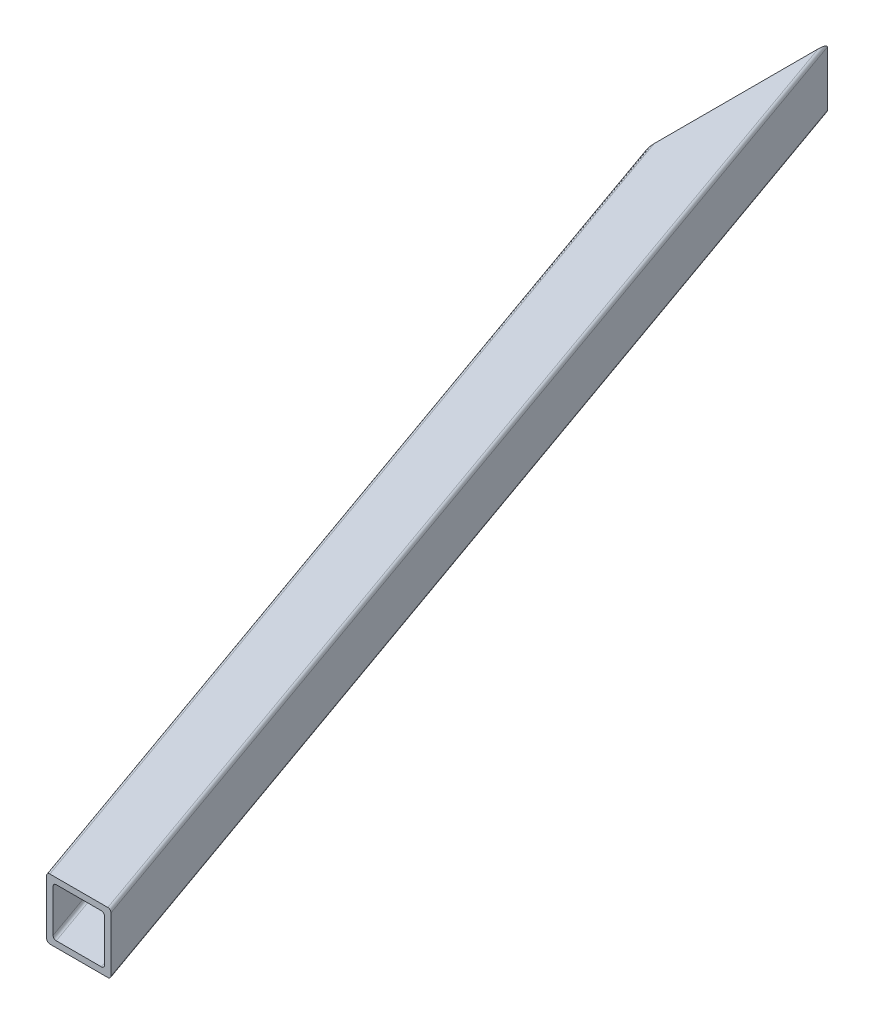
SolidWorks part; units mm, degrees
ref_plane "Plan de face" through (0, 0, 0) normal (0, 0, 1) x (1, 0, 0)
ref_plane "Plan de dessus" through (0, 0, 0) normal (0, 1, 0) x (1, 0, 0)
ref_plane "Plan de droite" through (0, 0, 0) normal (1, 0, 0) x (0, 0, -1)
sketch "Esquisse1" plane through (0, 0, 0) normal (0, 1, 0) x (1, 0, 0)
  line L0 (0, 0) -> (0, 609.9611) construction
  line L1 (0, 609.9611) -> (215.5753, 0)
  line L2 (215.5753, 0) -> (0, 0) construction
  line L3 (215.5753, 0) -> (258, 0)
  line L4 (258, 0) -> (0, 730)
  line L5 (0, 609.9611) -> (0, 730)
  dimension "D1" = 40
  dimension "D2" = 258
  dimension "D3" = 730
extrude "Boss.-Extru.1" add sketch "Esquisse1" along normal blind 40
shell "Coque1" thickness 4
ref_plane "Plan1" through (23.9373, 0, 67.7296) normal (-0.3332, 0, -0.9428) x (0, -1, 0)
sketch "Esquisse2" plane through (23.9373, 0, 67.7296) normal (-0.3332, 0, -0.9428) x (0, -1, 0)
  line L0 (-40, -243.2546) -> (-40, -203.2546) construction
  line L1 (-36, -207.2546) -> (-4, -207.2546)
  line L2 (-36, -207.2546) -> (-36, -239.2546)
  line L3 (-36, -239.2546) -> (-4, -239.2546)
  line L4 (-4, -207.2546) -> (-4, -239.2546)
  line L5 (-40, -203.2546) -> (0, -203.2546) construction
  line L6 (-40, -243.2546) -> (0, -243.2546) construction
  line L7 (0, -243.2546) -> (0, -203.2546) construction
  dimension "D1" = 4
  dimension "D2" = 4
  dimension "D3" = 4
  dimension "D4" = 4
extrude "Enlèv. mat.-Extru.1" cut sketch "Esquisse2" against normal through all both and the other way through all
fillet "Congé1" radius 2 8 edges at (107.7877, 40, -304.9806) (126.8788, 36, -358.9981) (109.9089, 36, -310.9825) (109.9089, 4, -310.9825) (126.8788, 4, -358.9981) (129, 40, -365) (107.7877, 0, -304.9806) (129, 0, -365)
